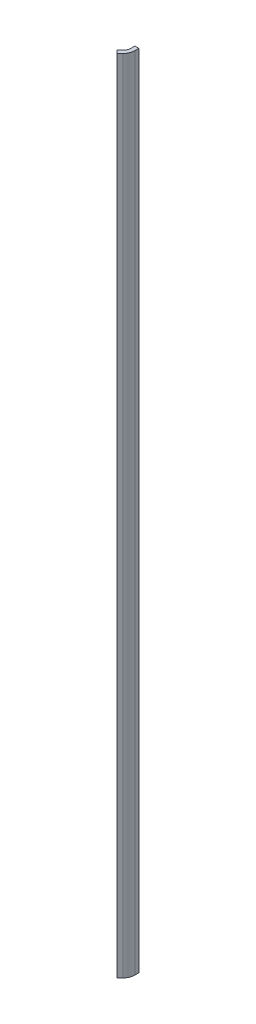
SolidWorks part; units mm, degrees
ref_plane "Front Plane" through (0, 0, 0) normal (0, 0, 1) x (1, 0, 0)
ref_plane "Top Plane" through (0, 0, 0) normal (0, 1, 0) x (1, 0, 0)
ref_plane "Right Plane" through (0, 0, 0) normal (1, 0, 0) x (0, 0, -1)
sketch "Sketch1" plane through (0, 0, 0) normal (0, 1, 0) x (1, 0, 0)
  line L5 (-70, 70.0441) -> (70, -70.0441) construction
  line L6 (-70, -70.0441) -> (70, 70.0441) construction
  line L7 (-68, 68.0441) -> (-68, 68.0428)
  line L10 (68, 68.0441) -> (68, 68.0428)
  line L16 (61.4142, -40.1446) -> (62.8284, -38.7304)
  line L17 (-68, -68.0428) -> (-68, -68.0441)
  line L18 (64, -33.9019) -> (64, -35.9019)
  line L19 (61.4142, -40.1446) -> (62.8284, -41.5588)
  line L20 (64, -33.9019) -> (66, -33.9019)
  line L27 (66, -33.9019) -> (66, -35.9019)
  line L29 (62.8284, -41.5588) -> (64.2426, -40.1446)
  arc A2 (64.2426, -40.1446) -> (66, -35.9019) centre (60, -35.9019) ccw
  arc A3 (62.8284, -38.7304) -> (64, -35.9019) centre (60, -35.9019) ccw
  point P0 (0, 0)
  point P7 (40, -70.0441)
  point P9 (67.0711, -42.973)
  point P10 (70, -35.9019)
  point P11 (70, -40.0441)
  point P14 (39.1716, -68.0441)
  point P15 (65.6569, -41.5588)
  point P17 (68, -35.9019)
  dimension "D1" = 2
extrude "Boss-Extrude3" add sketch "Sketch1" along normal blind 400 contours L20 L27 A2 L29 L19 L16 A3 L18
